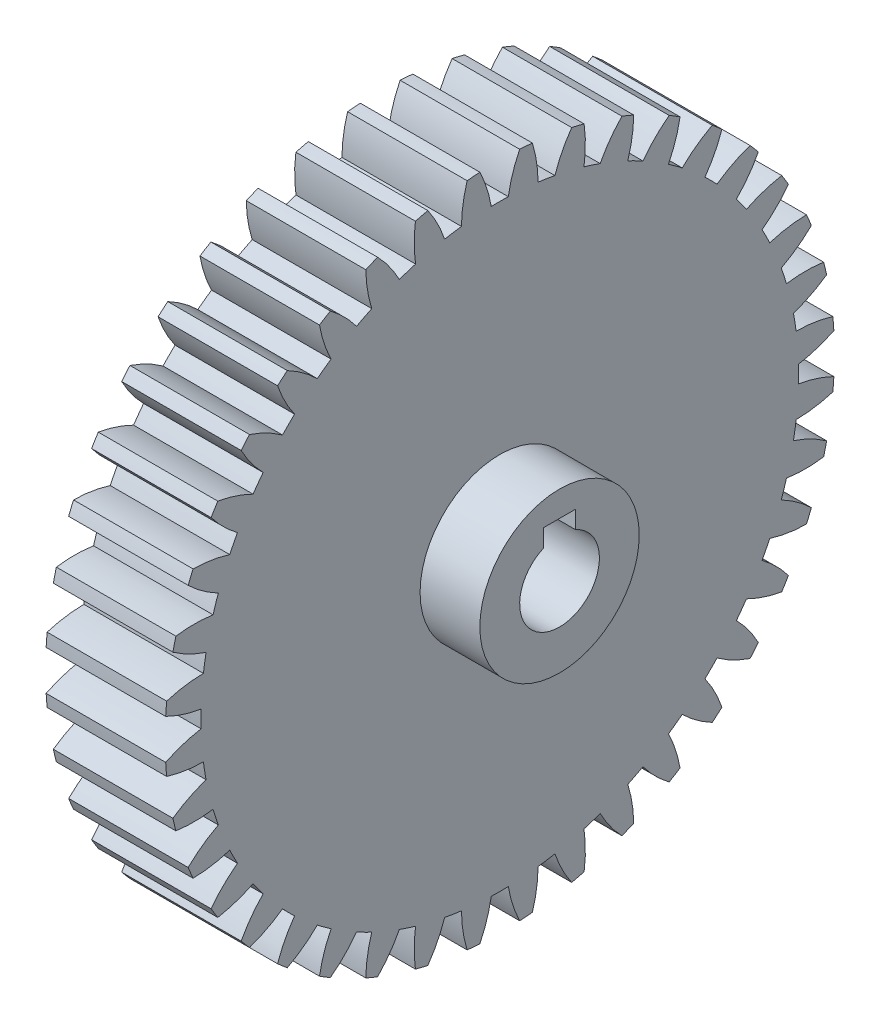
SolidWorks part; units mm, degrees
ref_plane "Plane1" through (0, 0, 0) normal (0, 0, 1) x (1, 0, 0)
ref_plane "Plane2" through (0, 0, 0) normal (0, 1, 0) x (1, 0, 0)
ref_plane "Plane3" through (0, 0, 0) normal (1, 0, 0) x (0, 0, -1)
sketch "HoldingSke" plane through (0, 0, 0) normal (0, 1, 0) x (1, 0, 0)
  line L0 (0, 0) -> (0.383, -0.3214)
  line L1 (-15, 0) -> (100, 0) construction
  line L2 (0, 0) -> (-2.1039, 2.3779)
  line L3 (0, 0) -> (-11.863, 4.5341)
  line L4 (0, 0) -> (6.6156, 5.5511)
  line L5 (0, 0) -> (-28.1086, -10.4837)
  line L6 (0, 0) -> (-12.4344, -8.3896)
  line L7 (-2.1039, 2.3779) -> (4.3536, 31.6747)
  line L8 (-76.2, 54.61) -> (-74.4, 54.61)
  line L9 (-67.7845, 28.3722) -> (-49.3413, 33.142)
  line L10 (-76.2, 71.12) -> (104.1128, 71.12)
  line L11 (0, 0) -> (-15, 0)
  line L12 (-76.2, 101.6) -> (-76.133, 101.6)
  line L13 (24.9733, 27.94) -> (52.9518, 28.4284)
  line L14 (24.9733, 27.94) -> (24.9743, 27.94)
  line L15 (24.9733, 27.94) -> (100.4006, 29.5858)
  line L16 (-63.627, -2) -> (-12.827, -2)
  circle A0 centre (0, 0) radius 5
  circle A1 centre (0, 0) radius 10
  circle A2 centre (0, 0) radius 10
  circle A3 centre (0, 0) radius 5
  dimension "MHD" = 20
  dimension "Hub_dia" = 20
  dimension "Bore" = 10
  dimension "MBD" = 10
  dimension "Num_teeth" = 40
  dimension "Pitch" = 0.5
  dimension "Overall_len" = 30
  dimension "Show_teeth" = 40
  dimension "Thickness" = 15
  dimension "OAL" = 30.0001
  dimension "T_dim" = 1.8
  dimension "Ap" = 14.5
  dimension "H" = 19.05
  dimension "Pitch_radius" = 180.3128
  dimension "Width" = 15
  dimension "Backlash" = 0.067
  dimension "Addendum_fac" = 1
  dimension "Dedendum_fac" = 1.25
  dimension "Clearance_fac" = 0.25
  dimension "Dedendum_add" = 0.001
  dimension "Module" = 2
sketch "BasProSke" plane through (0, 0, 0) normal (0, 1, 0) x (1, 0, 0)
  line L0 (-10, 0) -> (60, 0) construction
  line L1 (0, 0) -> (0, 42)
  line L2 (0, 0) -> (15, 0)
  line L3 (15, 0) -> (15, 42)
  line L4 (15, 42) -> (0, 42)
  dimension "Thickness" = 15
  dimension "Diameter" = 84
revolve "Base-Revolve" add sketch "BasProSke" angle 360 about L0
sketch "TooCutSke" plane through (0, 0, 0) normal (1, 0, 0) x (0, 0, -1)
  line L1 (0, 0) -> (0, 107) construction
  line L2 (0, 0) -> (-1.6876, 39.9644) construction
  line L3 (0, 0) -> (-6.2726, 79.7007) construction
  line L4 (-1.6876, 39.9644) -> (-3.1363, 39.8504) construction
  arc A0 (1.0692, 37.4838) -> (-1.0692, 37.4838) centre (0, 0) ccw
  arc A1 (2.5075, 41.9505) -> (-2.5075, 41.9505) centre (0, 0) ccw
  circle A2 centre (0, 0) radius 40 construction
  circle A3 centre (0, 0) radius 38.7259 construction
  arc A4 (-1.0692, 37.4838) -> (-2.5075, 41.9505) centre (-16.8537, 34.8662) ccw
  arc A5 (2.5075, 41.9505) -> (1.0692, 37.4838) centre (16.8537, 34.8662) ccw
  dimension "Root_dia" = 74.998
  dimension "Overcut_dia" = 84.0508
  dimension "Pitch_dia" = 80
  dimension "Base_dia" = 77.4518
  dimension "Flank_rad" = 16
  dimension "Half_ang" = 4.5
  dimension "Half_CT" = 1.4531
extrude "ToothCut" cut sketch "TooCutSke" along normal through all
fillet "Breaks" [suppressed] radius 0.04
fillet "RootFillets" [suppressed] radius 0.501
pattern_circular "TeethCuts" count 40 every 9 about axis through (-10, 0, 0) along (1, 0, 0) of "ToothCut", "RootFillets", "Breaks"
sketch "HubNeaOneSke" plane through (0, 0, 0) normal (-1, 0, 0) x (0, 0, 1)
  circle A0 centre (0, 0) radius 10
  dimension "Diameter" = 20
extrude "HubNearOne" [suppressed] add sketch "HubNeaOneSke" along normal blind 15.0001
sketch "HubNeaBotSke" plane through (0, 0, 0) normal (-1, 0, 0) x (0, 0, 1)
  circle A0 centre (0, 0) radius 10
  dimension "Diameter" = 20
extrude "HubNearBoth" add sketch "HubNeaBotSke" along normal blind 7.5
ref_plane "FarPln" through (15, 0, 0) normal (1, 0, 0) x (0, 0, -1)
sketch "HubFarSke" plane through (15, 0, 0) normal (1, 0, 0) x (0, 0, -1)
  circle A0 centre (0, 0) radius 10
  dimension "Diameter" = 20
extrude "HubFar" add sketch "HubFarSke" along normal blind 7.5
sketch "BorSke" plane through (0, 0, 0) normal (1, 0, 0) x (0, 0, -1)
  circle A0 centre (0, 0) radius 5
  dimension "Diameter" = 10
extrude "Bore" cut sketch "BorSke" along normal mid plane 60.0001
sketch "KeySke" plane through (0, 0, 0) normal (1, 0, 0) x (0, 0, -1)
  line L0 (-2, 0) -> (-2, 6.8)
  line L1 (-2, 6.8) -> (2, 6.8)
  line L2 (2, 6.8) -> (2, 0)
  line L3 (0, 0) -> (0, 34) construction
  line L4 (-2, 0) -> (2, 0)
  dimension "Offset" = 6.8
  dimension "Width" = 4
extrude "Keyway" cut sketch "KeySke" along normal mid plane 60.0001
pattern_circular "Keyway2" [suppressed] count 2 every 90 about axis through (-10, 0, 0) along (1, 0, 0)
equation "' \"Module@HoldingSke\" = 6.35"
equation "' \"Num_teeth@HoldingSke\" = 12"
equation "' \"Ap@HoldingSke\" =  20"
equation "' \"Ap@HoldingSke\" = 20"
equation "' \"Width@HoldingSke\" = 0.5 * 25.4"
equation "' \"Hub_dia@HoldingSke\"= 1 * 25.4"
equation "' \"Hub_dia@HoldingSke\" = 1 * 25.4"
equation "' \"Overall_len@HoldingSke\" = 1.0 * 25.4"
equation "' \"Bore@HoldingSke\" = 0.75 * 25.4"
equation "' \"T_dim@HoldingSke\" = 0.1 * 25.4"
equation "' \"Width@KeySke\" = 0.25 * 25.4"
equation "' \"Show_teeth@HoldingSke\" = 13"
equation "' \"Backlash@HoldingSke\" = 0.009 * 25.4"
equation "' \"Addendum_fac@HoldingSke\" = 1.0"
equation "' \"Dedendum_fac@HoldingSke\" = 1.25"
equation "' \"Dedendum_add@HoldingSke\" = 0.00005 * 25.4"
equation "' \"Clearance_fac@HoldingSke\" = 0.25"
equation "\"Pitch@HoldingSke\" = 1 / \"Module@HoldingSke\""
equation "\"Overcut_dia@TooCutSke\" = (\"Num_teeth@HoldingSke\" + 2 * \"Addendum_fac@HoldingSke\") / \"Pitch@HoldingSke\" + 0.002 * 25.4"
equation "\"Pitch_dia@TooCutSke\" = \"Num_teeth@HoldingSke\" / \"Pitch@HoldingSke\""
equation "\"Base_dia@TooCutSke\" = \"Num_teeth@HoldingSke\" / \"Pitch@HoldingSke\" * cos((\"Ap@HoldingSke\"  * 3.14159265 / 180))"
equation "\"Root_dia@TooCutSke\" = (\"Num_teeth@HoldingSke\" + 2) / \"Pitch@HoldingSke\" - 2 * (\"Addendum_fac@HoldingSke\" + \"Dedendum_fac@HoldingSke\") / \"Pitch@HoldingSke\" - \"Dedendum_add@HoldingSke\" * 2"
equation "\"Half_ang@TooCutSke\" = 180 / \"Num_teeth@HoldingSke\""
equation "\"Half_CT@TooCutSke\" = \"Num_teeth@HoldingSke\" / \"Pitch@HoldingSke\" * sin((3.14159265 / 2 / \"Num_teeth@HoldingSke\")) / 2 - 7 * \"Backlash@HoldingSke\" / 4"
equation "\"Flank_rad@TooCutSke\" = \"Num_teeth@HoldingSke\" / \"Pitch@HoldingSke\" / 5"
equation "\"Radius@RootFillets\" = \"Clearance_fac@HoldingSke\" / \"Pitch@HoldingSke\" + \"Dedendum_add@HoldingSke\""
equation "\"Break_rad@Breaks\" = 0.02 / \"Pitch@HoldingSke\""
equation "\"Thickness@HoldingSke\" = \"Width@HoldingSke\""
equation "\"OAL@HoldingSke\" = \"Thickness@HoldingSke\""
equation "\"MHD@HoldingSke\" = (\"Num_teeth@HoldingSke\" + 2) / \"Pitch@HoldingSke\" - 2 * (\"Addendum_fac@HoldingSke\" + \"Dedendum_fac@HoldingSke\")  / \"Pitch@HoldingSke\" - \"Dedendum_add@HoldingSke\" * 2"
equation "\"MBD@HoldingSke\" = (\"Num_teeth@HoldingSke\" + 2) / \"Pitch@HoldingSke\" - 2 * (\"Addendum_fac@HoldingSke\" + \"Dedendum_fac@HoldingSke\")  / \"Pitch@HoldingSke\" - \"Dedendum_add@HoldingSke\" * 2 - 0.002 * 25.4"
equation "\"MHD@HoldingSke\" = ((sgn( \"MHD@HoldingSke\" - \"Hub_dia@HoldingSke\" )-1)*( \"MHD@HoldingSke\" - \"Hub_dia@HoldingSke\" ))/-2+ \"Hub_dia@HoldingSke\""
equation "\"MBD@HoldingSke\" = ((sgn( \"MBD@HoldingSke\" - \"Bore@HoldingSke\" )-1)*( \"MBD@HoldingSke\" - \"Bore@HoldingSke\" ))/-2+ \"Bore@HoldingSke\""
equation "\"OAL@HoldingSke\" = ((sgn( \"OAL@HoldingSke\" - \"Overall_len@HoldingSke\" )+1)*( \"OAL@HoldingSke\" - \"Overall_len@HoldingSke\" ))/2 + \"Overall_len@HoldingSke\" + 0.000002 * 25.4"
equation "\"Num_teeth@TeethCuts\" = int( \"Show_teeth@HoldingSke\" ) + 1"
equation "\"Num_teeth@TeethCuts\" = ((sgn( \"Num_teeth@TeethCuts\" - \"Num_teeth@HoldingSke\" )-1)*( \"Num_teeth@TeethCuts\" - \"Num_teeth@HoldingSke\" ))/-2+ \"Num_teeth@HoldingSke\""
equation "\"Num_teeth@TeethCuts\" = ((sgn( \"Num_teeth@TeethCuts\" - 2.0)+1)*( \"Num_teeth@TeethCuts\" - 2.0))/2 +2.0"
equation "\"Angle@TeethCuts\" = 360.0 / \"Num_teeth@HoldingSke\""
equation "\"Diameter@BasProSke\" = (\"Num_teeth@HoldingSke\" + 2 * \"Addendum_fac@HoldingSke\") / \"Pitch@HoldingSke\""
equation "\"Thickness@BasProSke\"  = \"Thickness@HoldingSke\""
equation "' \"Fillet_rad@BasProSke\" =  \"Thickness@HoldingSke\" * 0.05"
equation "' \"Fillet_rad@BasProSke\" = \"Thickness@HoldingSke\" * 0.05"
equation "\"MHD@HoldingSke\" = ((sgn( \"MHD@HoldingSke\" - \"Root_dia@TooCutSke\" )-1)*( \"MHD@HoldingSke\" - \"Root_dia@TooCutSke\" ))/-2+ \"Root_dia@TooCutSke\""
equation "\"Diameter@HubNeaOneSke\" = \"MHD@HoldingSke\""
equation "\"Length@HubNearOne\" = \"OAL@HoldingSke\" - \"Thickness@BasProSke\""
equation "\"Diameter@HubNeaBotSke\" = \"MHD@HoldingSke\""
equation "\"Length@HubNearBoth\" = ( \"OAL@HoldingSke\" - \"Thickness@BasProSke\" ) / 2.0"
equation "\"Thickness@FarPln\" = \"Thickness@BasProSke\""
equation "\"Diameter@HubFarSke\" = \"MHD@HoldingSke\""
equation "\"Length@HubFar\" = ( \"OAL@HoldingSke\" - \"Thickness@BasProSke\" ) / 2.0"
equation "\"Diameter@BorSke\" = \"MBD@HoldingSke\""
equation "\"D1@Bore\" = \"OAL@HoldingSke\" * 2.0"
equation "\"D1@Keyway\" = \"OAL@HoldingSke\" * 2.0"
equation "\"Offset@KeySke\" = \"T_dim@HoldingSke\" + \"MBD@HoldingSke\" / 2.0"
